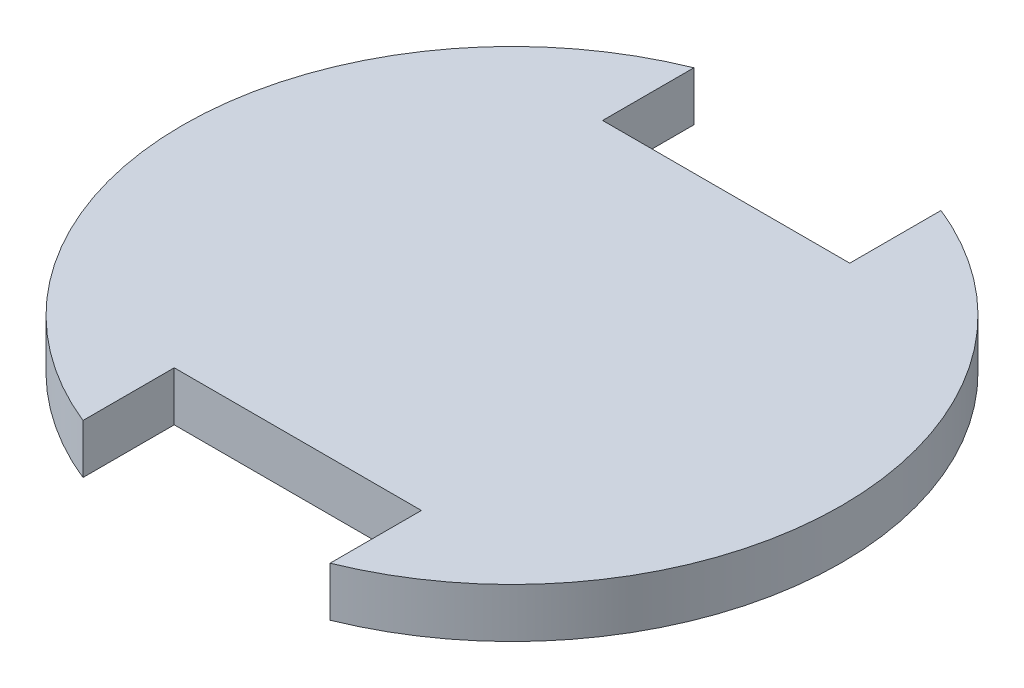
SolidWorks part; units mm, degrees
ref_plane "Front Plane" through (0, 0, 0) normal (0, 0, 1) x (1, 0, 0)
ref_plane "Top Plane" through (0, 0, 0) normal (0, 1, 0) x (1, 0, 0)
ref_plane "Right Plane" through (0, 0, 0) normal (1, 0, 0) x (0, 0, -1)
sketch "Sketch1" plane through (0, 0, 0) normal (0, 1, 0) x (1, 0, 0)
  circle A0 centre (0, 0) radius 20
  dimension "D1" = 40
extrude "Boss-Extrude1" add sketch "Sketch1" along normal mid plane 3
sketch "Sketch2" plane through (0, -1.5, 0) normal (0, -1, 0) x (1, 0, 0)
  line L0 (0, -44.7868) -> (0, 44.7868) construction
  ellipse E0 centre (0, 0) end of major axis (0, -10) minor radius 5
  dimension "D1" = 10
  dimension "D2" = 20
sketch "Sketch3" plane through (0, 1.5, 0) normal (0, 1, 0) x (1, 0, 0)
  line L0 (0, -44.7868) -> (0, 44.7868) construction
  line L1 (-7.5, 23) -> (7.5, 23)
  line L2 (-7.5, 23) -> (-7.5, 13)
  line L3 (-7.5, 13) -> (7.5, 13)
  line L4 (7.5, 23) -> (7.5, 13)
  line L5 (-44.2539, 0) -> (44.2539, 0) construction
  dimension "D1" = 15
  dimension "D2" = 10
  dimension "D3" = 7.5
  dimension "D4" = 13
extrude "Cut-Extrude2" cut sketch "Sketch3" against normal up to surface (3 mm away) up to face at (0, -1.5, 20)
mirror "Mirror1" about plane through (0, 0, 0) normal (0, 0, 1) of "Cut-Extrude2"
